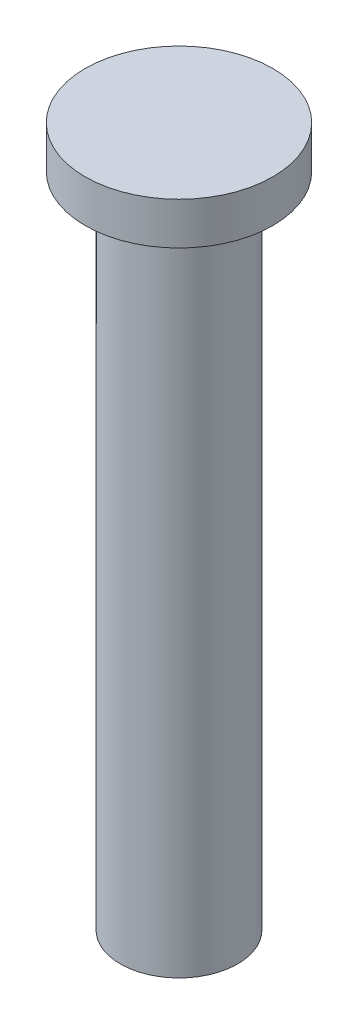
SolidWorks part; units mm, degrees
material "AISI 304"
ref_plane "前视基准面" through (0, 0, 0) normal (0, 0, 1) x (1, 0, 0)
ref_plane "上视基准面" through (0, 0, 0) normal (0, 1, 0) x (1, 0, 0)
ref_plane "右视基准面" through (0, 0, 0) normal (1, 0, 0) x (0, 0, -1)
sketch "草图1" plane through (0, 0, 0) normal (0, 0, 1) x (1, 0, 0)
  line L0 (0, 0) -> (0, -14.9)
  line L1 (0, -14.9) -> (1.25, -14.9)
  line L2 (1.25, -14.9) -> (1.25, -0.9)
  line L3 (1.25, -0.9) -> (2, -0.9)
  line L4 (2, -0.9) -> (2, 0)
  line L5 (2, 0) -> (0, 0)
  dimension "D1" = 0.9
  dimension "D2" = 2
  dimension "D3" = 14
  dimension "D4" = 1.25
revolve "旋转1" add sketch "草图1" angle 360 about L0
